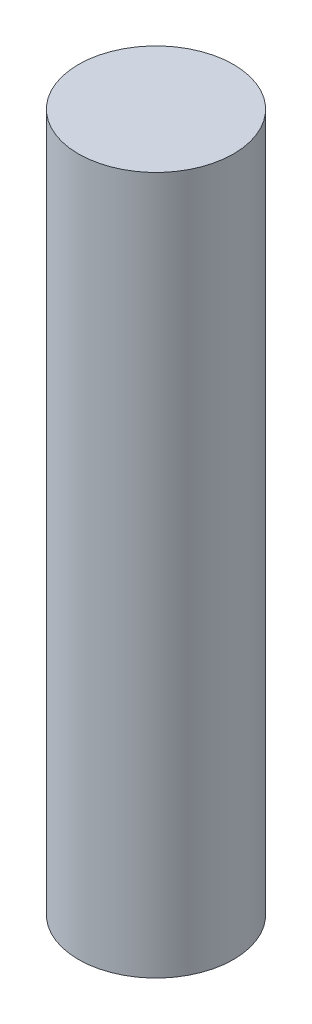
SolidWorks part; units mm, degrees
ref_plane "Front Plane" through (0, 0, 0) normal (0, 0, 1) x (1, 0, 0)
ref_plane "Top Plane" through (0, 0, 0) normal (0, 1, 0) x (1, 0, 0)
ref_plane "Right Plane" through (0, 0, 0) normal (1, 0, 0) x (0, 0, -1)
sketch "Sketch1" plane through (0, 0, 0) normal (0, 1, 0) x (1, 0, 0)
  circle A0 centre (0, 0) radius 1
  dimension "D1" = 2
extrude "Boss-Extrude1" add sketch "Sketch1" along normal mid plane 9
ref_plane "Plane1" through (0, 0, 0) normal (0, 1, 0) x (1, 0, 0)
